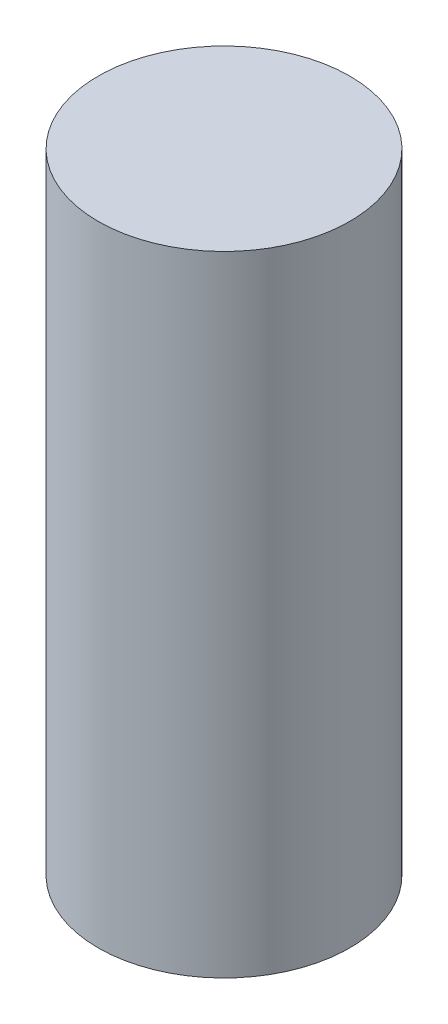
SolidWorks part; units mm, degrees
ref_plane "Front Plane" through (0, 0, 0) normal (0, 0, 1) x (1, 0, 0)
ref_plane "Top Plane" through (0, 0, 0) normal (0, 1, 0) x (1, 0, 0)
ref_plane "Right Plane" through (0, 0, 0) normal (1, 0, 0) x (0, 0, -1)
sketch "Sketch1" plane through (0, 0, 0) normal (0, 1, 0) x (1, 0, 0)
  circle A0 centre (0, 0) radius 4
  dimension "D1" = 8
extrude "Boss-Extrude1" add sketch "Sketch1" along normal mid plane 20
